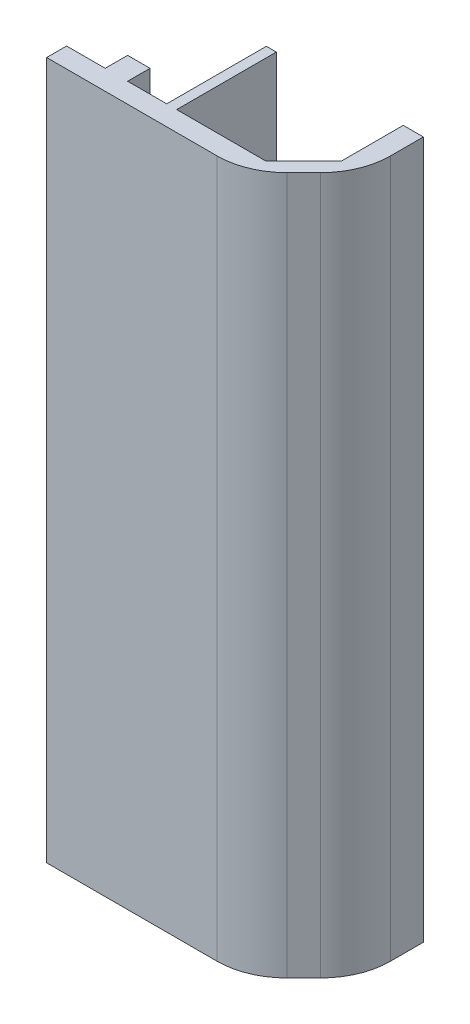
SolidWorks part; units mm, degrees
ref_plane "前基準面" through (0, 0, 0) normal (0, 0, 1) x (1, 0, 0)
ref_plane "上基準面" through (0, 0, 0) normal (0, 1, 0) x (1, 0, 0)
ref_plane "右基準面" through (0, 0, 0) normal (1, 0, 0) x (0, 0, -1)
sketch "草圖1" plane through (0, 0, 0) normal (0, 1, 0) x (1, 0, 0)
  line L0 (-27.5017, 6.8593) -> (-23.0017, 6.8593)
  line L1 (-23.0017, 6.8593) -> (-23.0017, 2.3593)
  line L2 (-23.0017, 2.3593) -> (4.7483, 2.3593)
  line L3 (4.7483, 2.3593) -> (12.3316, 9.9426)
  line L4 (12.3316, 9.9426) -> (12.3316, 22.3593)
  line L5 (-27.5017, 6.8593) -> (-27.5017, 2.3593)
  line L6 (-27.5017, 2.3593) -> (-35.2517, 2.3593)
  line L7 (-35.2517, 2.3593) -> (-35.2517, -1.6407)
  line L8 (-35.2517, -1.6407) -> (4.7783, -1.6407)
  line L12 (4.7783, -1.6407) -> (16.3616, 9.9426)
  line L13 (12.3316, 22.3593) -> (16.3616, 22.3593)
  line L14 (16.3616, 22.3593) -> (16.3616, 9.9426)
  dimension "D1" = 4.5
  dimension "D2" = 4.5
  dimension "D3" = 4
  dimension "D4" = 4
  dimension "D5" = 7.75
  dimension "D6" = 27.75
  dimension "D7" = 20
extrude "填料-伸長1" add sketch "草圖1" along normal blind 140
fillet "圓角1" radius 14 2 edges at (4.7783, 70, 1.6407) (16.3616, 70, -9.9426)
sketch "草圖2" plane through (0, 0, -2.3593) normal (0, 0, -1) x (-1, 0, 0)
  line L0 (-4.7483, 140) -> (23.0017, 140) construction
  line L1 (13.1517, 140) -> (15.1517, 140)
  line L2 (13.1517, 140) -> (13.1517, 0)
  line L3 (13.1517, 0) -> (15.1517, 0)
  line L4 (15.1517, 140) -> (15.1517, 0)
  line L5 (-4.7483, 0) -> (23.0017, 0) construction
  line L6 (35.2517, 140) -> (35.2517, 0) construction
  dimension "D1" = 20.1
  dimension "D2" = 2
extrude "填料-伸長2" add sketch "草圖2" along normal blind 20
